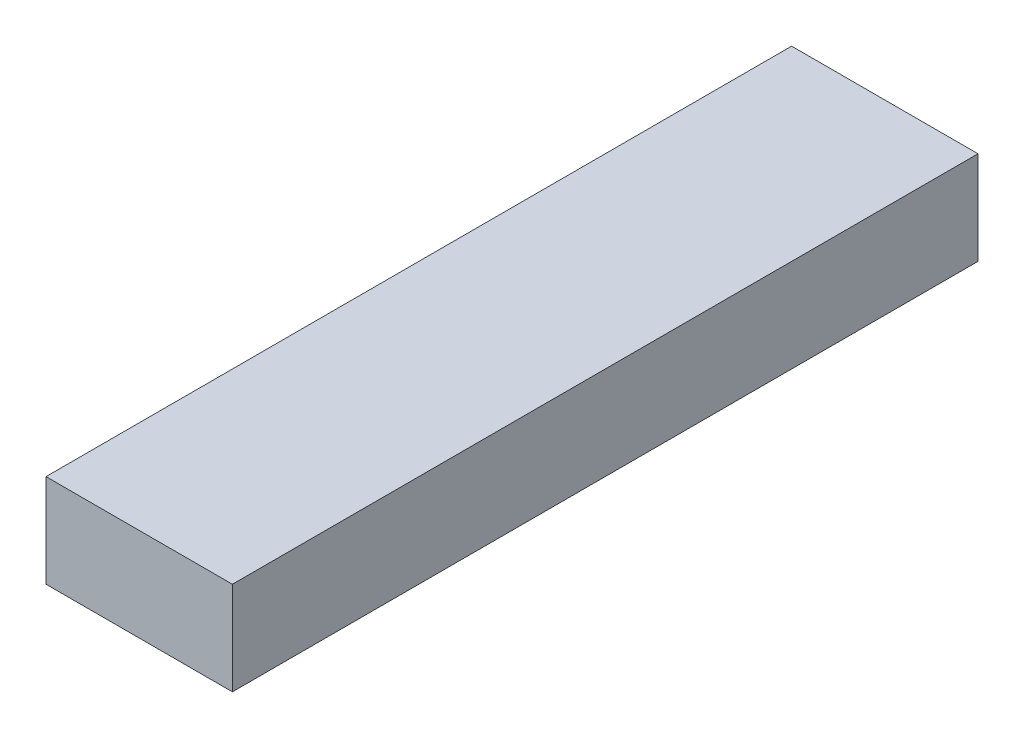
SolidWorks part; units mm, degrees
ref_plane "前视基准面" through (0, 0, 0) normal (0, 0, 1) x (1, 0, 0)
ref_plane "上视基准面" through (0, 0, 0) normal (0, 1, 0) x (1, 0, 0)
ref_plane "右视基准面" through (0, 0, 0) normal (1, 0, 0) x (0, 0, -1)
other "Configuration Table"
sketch "Profile1" plane through (0, 0, 0) normal (0, 0, 1) x (1, 0, 0)
  line L1 (-5, -2.5) -> (5, -2.5)
  line L2 (-5, -2.5) -> (-5, 2.5)
  line L3 (-5, 2.5) -> (5, 2.5)
  line L4 (5, -2.5) -> (5, 2.5)
sketch "Path1" plane through (0, 0, 0) normal (1, 0, 0) x (0, 0, -1)
  line L0 (0, 0) -> (-40, 0)
sweep "sweep_profile_rect" add profiles "Profile1" path "Path1"
